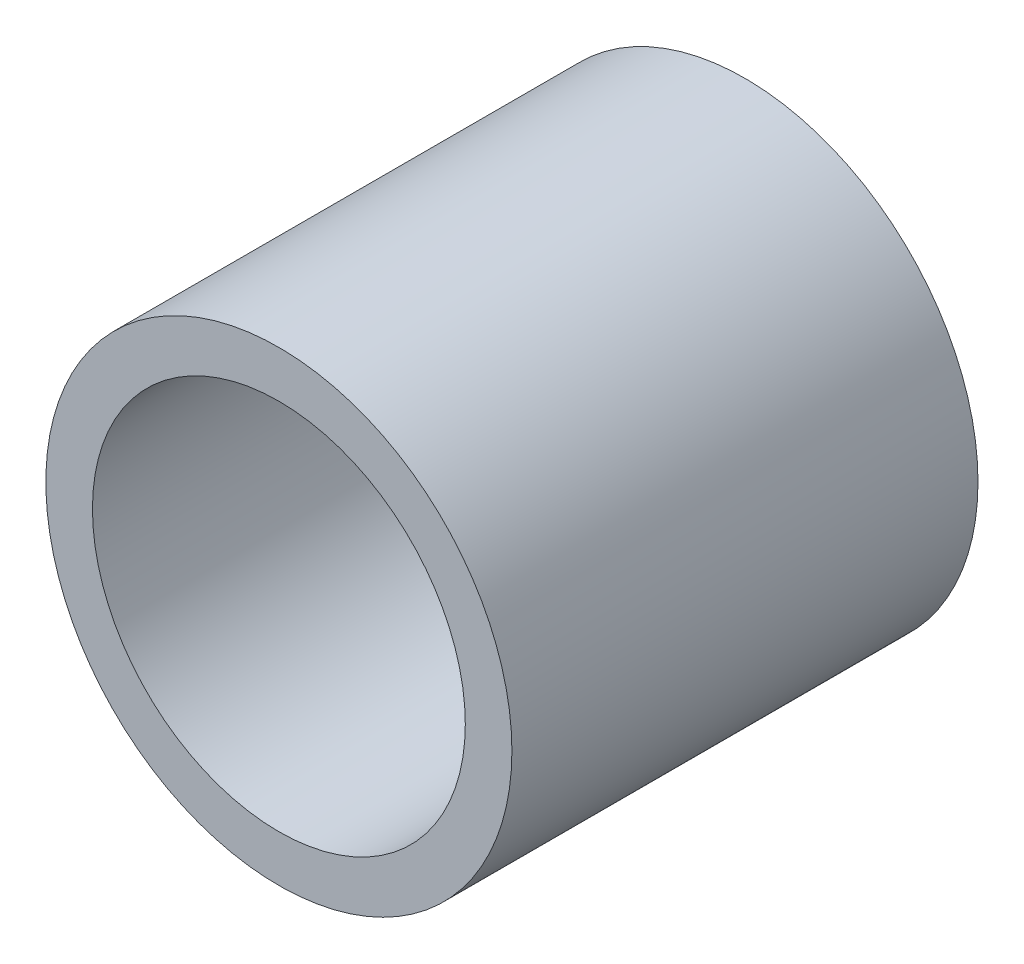
SolidWorks part; units mm, degrees
material "Brass"
ref_plane "Front Plane" through (0, 0, 0) normal (0, 0, 1) x (1, 0, 0)
ref_plane "Top Plane" through (0, 0, 0) normal (0, 1, 0) x (1, 0, 0)
ref_plane "Right Plane" through (0, 0, 0) normal (1, 0, 0) x (0, 0, -1)
sketch "Sketch1" plane through (0, 0, 0) normal (0, 0, 1) x (1, 0, 0)
  circle A0 centre (0, 0) radius 6.35
  circle A1 centre (0, 0) radius 7.9375
  dimension "D1" = 15.875
  dimension "D2" = 12.7
extrude "Boss-Extrude1" add sketch "Sketch1" along normal mid plane 15.875
